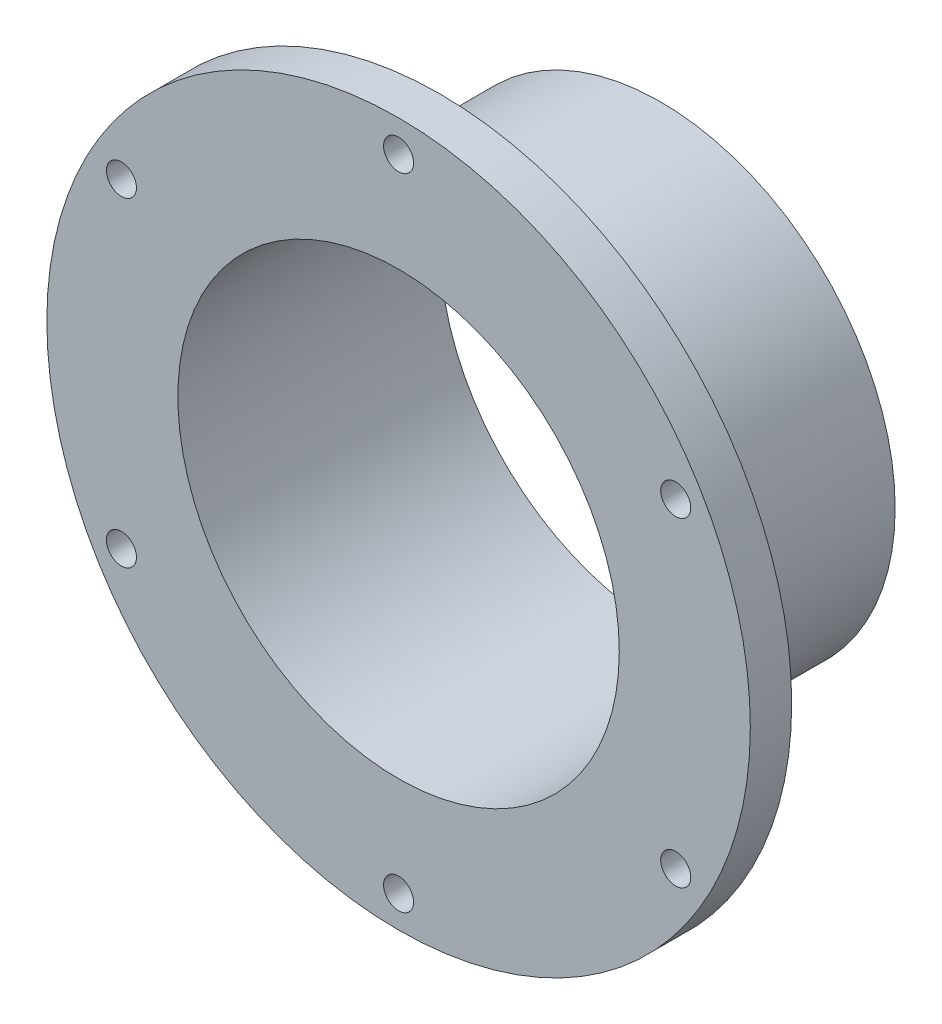
SolidWorks part; units mm, degrees
material "6061-T6 (SS)"
ref_plane "Front Plane" through (0, 0, 0) normal (0, 0, 1) x (1, 0, 0)
ref_plane "Top Plane" through (0, 0, 0) normal (0, 1, 0) x (1, 0, 0)
ref_plane "Right Plane" through (0, 0, 0) normal (1, 0, 0) x (0, 0, -1)
sketch "Sketch1" plane through (0, 0, 0) normal (0, 0, 1) x (1, 0, 0)
  circle A0 centre (0, 0) radius 26.9875
  circle A1 centre (0, 0) radius 25.4
  dimension "D1" = 50.8
  dimension "D2" = 1.5875
extrude "Boss-Extrude1" add sketch "Sketch1" along normal blind 25.4
sketch "Sketch2" plane through (0, 0, 25.4) normal (0, 0, 1) x (1, 0, 0)
  circle A0 centre (0, 0) radius 25.4
  circle A1 centre (0, 0) radius 40.4813
  circle A2 centre (0, 0) radius 25.4 construction
  dimension "D1" = 80.9625
extrude "Boss-Extrude2" add sketch "Sketch2" along normal blind 4.7625
fillet "Fillet1" radius 5.08 1 edges at (26.9875, 0, 25.4)
sketch "Sketch3" plane through (0, 0, 30.1625) normal (0, 0, 1) x (1, 0, 0)
  circle A0 centre (0, 0) radius 35.56
  dimension "D1" = 71.12
sketch "Sketch4" plane through (0, 0, 30.1625) normal (0, 0, 1) x (1, 0, 0)
  circle A0 centre (0, 0) radius 36.83 construction
  dimension "D1" = 73.66
hole_wizard "#8-32 Tapped Hole1" positions "Sketch6" profile "Sketch7" tap size "#8-32" standard "ANSI Inch"
sketch "Sketch6" plane through (0, 0, 30.1625) normal (0, 0, 1) x (1, 0, 0)
  line L2 (0, 0) -> (0, 36.83) construction
  circle A0 centre (0, 0) radius 36.83 construction
  point P0 (0, 36.83)
sketch "Sketch7" plane through (0, 36.83, 30.1625) normal (1, 0, 0) x (0, -1, 0)
  line L0 (0, 0) -> (0, 11.7058)
  line L1 (0, 11.7058) -> (1.7272, 10.668)
  line L2 (1.7272, 10.668) -> (1.7272, 0)
  line L5 (1.7272, 0) -> (0, 0)
  line L10 (0, 11.7058) -> (-1.7272, 10.668) construction
  line L11 (0, -6.35) -> (0, 107.95) construction
  dimension "Tap Drill Dia." = 3.4544
  dimension "Tap Drill Depth" = 10.668
  dimension "Drill Angle" = 118
cosmetic thread "Hole Thread1" parameters "D1"=4.7625, "D2"=4.1656
pattern_circular "CirPattern1" count 6 over 360 about axis through (0, 0, 0) along (0, 0, 1) of "#8-32 Tapped Hole1"
